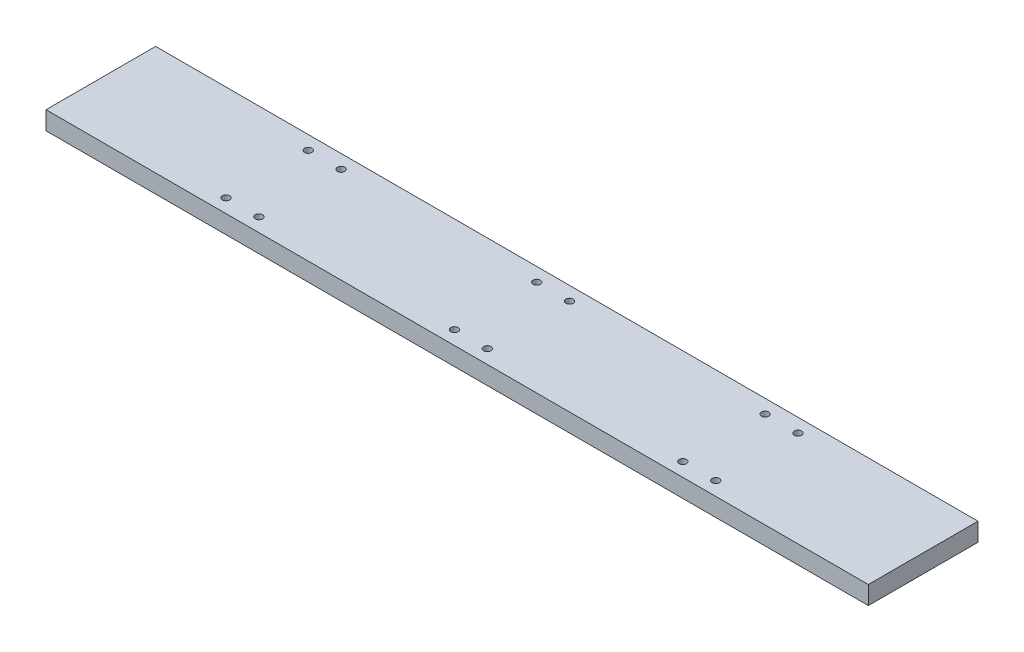
SolidWorks part; units mm, degrees
ref_plane "Plano frontal" through (0, 0, 0) normal (0, 0, 1) x (1, 0, 0)
ref_plane "Plano superior" through (0, 0, 0) normal (0, 1, 0) x (1, 0, 0)
ref_plane "Plano direito" through (0, 0, 0) normal (1, 0, 0) x (0, 0, -1)
sketch "Esboço1" plane through (0, 0, 0) normal (0, 1, 0) x (1, 0, 0)
  line L1 (-225, -30) -> (225, -30)
  line L2 (-225, -30) -> (-225, 30)
  line L3 (-225, 30) -> (225, 30)
  line L4 (225, -30) -> (225, 30)
  line L5 (-225, -30) -> (225, 30) construction
  line L6 (-225, 30) -> (225, -30) construction
  point P0 (0, 0)
  dimension "D1" = 450
  dimension "D2" = 60
extrude "Ressalto-extrusão1" add sketch "Esboço1" along normal blind 10
sketch "Esboço2" plane through (0, 10, 0) normal (0, 1, 0) x (1, 0, 0)
  line L0 (0, 0) -> (0, 69.5934) construction
  line L1 (125, 30) -> (125, -30) construction
  line L2 (225, 30) -> (-225, 30) construction
  line L3 (-225, -30) -> (225, -30) construction
  line L4 (225, 0) -> (-225, 0) construction
  line L5 (225, -30) -> (225, 30) construction
  line L6 (-225, 30) -> (-225, -30) construction
  circle A0 centre (9, 22.5) radius 2
  circle A1 centre (116, 22.5) radius 2
  circle A2 centre (134, 22.5) radius 2
  circle A3 centre (134, -22.5) radius 2
  circle A4 centre (116, -22.5) radius 2
  circle A5 centre (9, -22.5) radius 2
  circle A6 centre (-116, 22.5) radius 2
  circle A7 centre (-134, 22.5) radius 2
  circle A8 centre (-134, -22.5) radius 2
  circle A9 centre (-116, -22.5) radius 2
  circle A10 centre (-9, -22.5) radius 2
  circle A11 centre (-9, 22.5) radius 2
  dimension "D2" = 4
  dimension "D3" = 4
  dimension "D4" = 18
  dimension "D5" = 45
  dimension "D6" = 18
  dimension "D7" = 45
  dimension "D1" = 125
extrude "Corte-extrusão1" cut sketch "Esboço2" against normal through all
